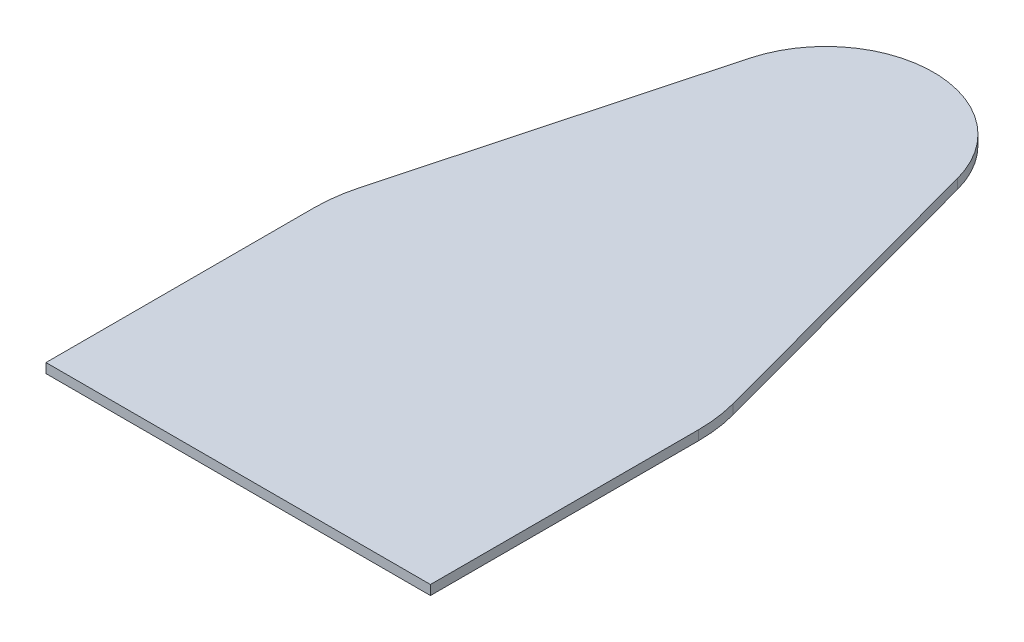
SolidWorks part; units mm, degrees
ref_plane "Front Plane" through (0, 0, 0) normal (0, 0, 1) x (1, 0, 0)
ref_plane "Top Plane" through (0, 0, 0) normal (0, 1, 0) x (1, 0, 0)
ref_plane "Right Plane" through (0, 0, 0) normal (1, 0, 0) x (0, 0, -1)
sketch "Sketch1" plane through (0, 0, 0) normal (0, 1, 0) x (1, 0, 0)
  line L0 (63.5, 229.647) -> (63.5, 0) construction
  line L1 (0, 0) -> (127, 0)
  line L2 (0, 0) -> (0, 88.5169)
  line L4 (127, 0) -> (127, 88.5169)
  line L9 (63.5, 139.7) -> (63.5, 116.7) construction
  line L10 (1.754, 101.7506) -> (29.1678, 203.3506)
  line L11 (97.8322, 203.3506) -> (125.246, 101.7506)
  arc A0 (29.1678, 203.3506) -> (97.8322, 203.3506) centre (63.5, 194.087) cw
  arc A1 (0, 88.5169) -> (1.754, 101.7506) centre (50.8, 88.5169) cw
  arc A2 (125.246, 101.7506) -> (127, 88.5169) centre (76.2, 88.5169) cw
  point P12 (0, 95.25)
  point P17 (35.2652, 187.1928)
  point P18 (63.5, 229.647)
  dimension "D3" = 35.56
  dimension "D4" = 50.8
  dimension "D5" = 50.8
  dimension "D1" = 127
  dimension "D2" = 95.25
  dimension "D6" = 101.6
extrude "Boss-Extrude2" add sketch "Sketch1" along normal blind 3.175
